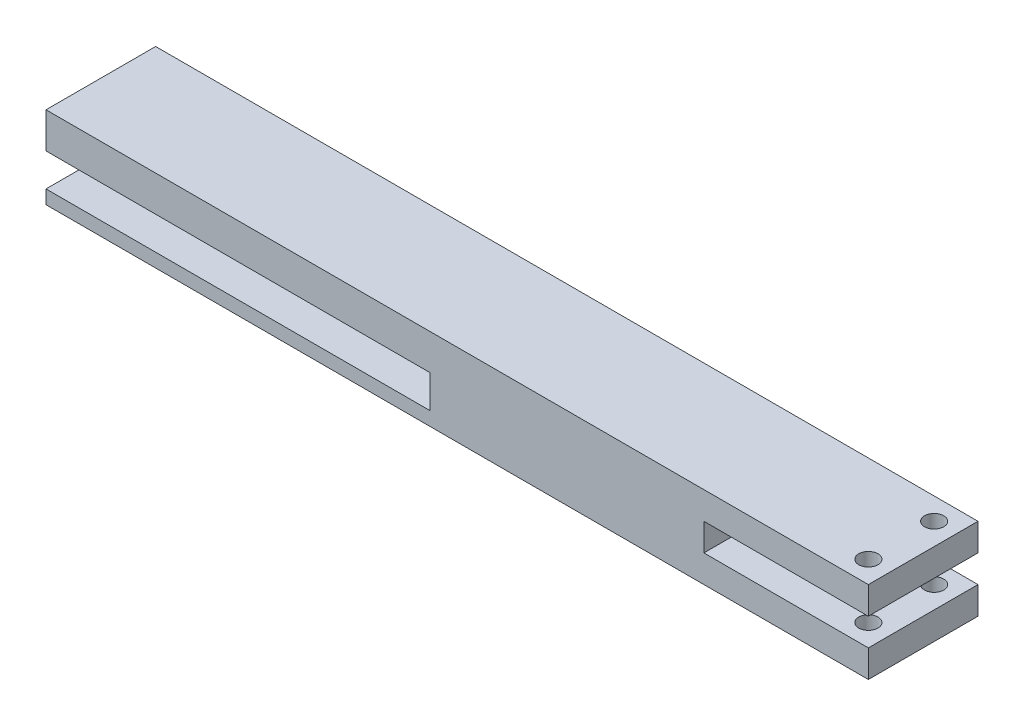
SolidWorks part; units mm, degrees
ref_plane "Front Plane" through (0, 0, 0) normal (0, 0, 1) x (1, 0, 0)
ref_plane "Top Plane" through (0, 0, 0) normal (0, 1, 0) x (1, 0, 0)
ref_plane "Right Plane" through (0, 0, 0) normal (1, 0, 0) x (0, 0, -1)
sketch "Sketch1" plane through (0, 0, 0) normal (0, 1, 0) x (1, 0, 0)
  line L0 (0, 0) -> (37420.0295, 0) construction
  line L1 (-81.2, 10) -> (68.8, 10)
  line L2 (68.8, 10) -> (68.8, -10)
  line L3 (68.8, -10) -> (-81.2, -10)
  line L4 (-81.2, -10) -> (-81.2, 10)
  dimension "D1" = 20
  dimension "D2" = 150
  dimension "D3" = 10
extrude "Boss-Extrude3" add sketch "Sketch1" against normal blind 15
sketch "Sketch11" plane through (0, 0, 10) normal (0, 0, 1) x (1, 0, 0)
  line L0 (-81.2, -15) -> (-81.2, 0) construction
  line L1 (-81.2, -6.5) -> (-11.2, -6.5)
  line L2 (-81.2, -6.5) -> (-81.2, -12.5)
  line L3 (-81.2, -12.5) -> (-11.2, -12.5)
  line L4 (-11.2, -6.5) -> (-11.2, -12.5)
  line L5 (-81.2, 0) -> (68.8, 0) construction
  dimension "D1" = 70
  dimension "D2" = 6.5
  dimension "D3" = 6
extrude "Cut-Extrude5" cut sketch "Sketch11" against normal through all
sketch "Sketch12" plane through (0, 0, 10) normal (0, 0, 1) x (1, 0, 0)
  line L0 (68.8, -15) -> (68.8, 0) construction
  line L1 (68.8, -5) -> (38.8, -5)
  line L2 (68.8, -5) -> (68.8, -10)
  line L3 (68.8, -10) -> (38.8, -10)
  line L4 (38.8, -5) -> (38.8, -10)
  line L5 (-81.2, 0) -> (68.8, 0) construction
  dimension "D1" = 30
  dimension "D2" = 5
  dimension "D3" = 5
extrude "Cut-Extrude6" cut sketch "Sketch12" against normal through all
sketch "Sketch13" plane through (0, 0, 0) normal (0, 1, 0) x (1, 0, 0)
  line L0 (-81.2, -10) -> (68.8, -10) construction
  line L1 (68.8, -10) -> (68.8, 10) construction
  line L2 (68.8, 10) -> (-81.2, 10) construction
  circle A0 centre (64.8, -6) radius 1.75
  circle A1 centre (64.8, 6) radius 1.75
  dimension "D1" = 3.5
  dimension "D2" = 4
  dimension "D3" = 4
  dimension "D4" = 4
extrude "Cut-Extrude7" cut sketch "Sketch13" against normal through all
